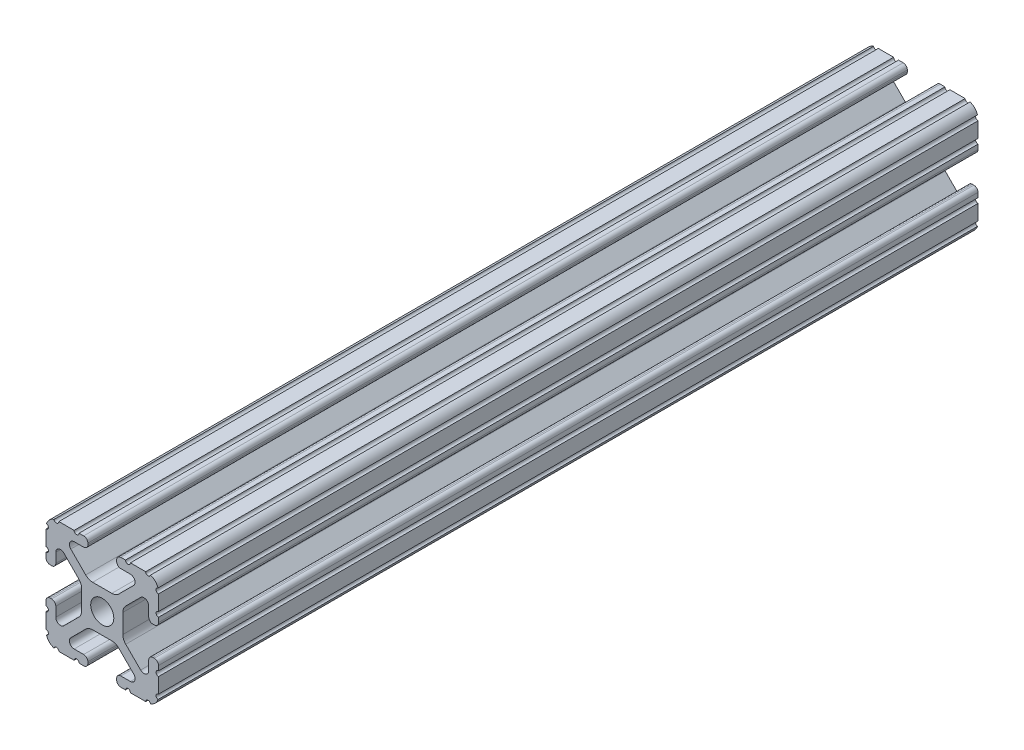
SolidWorks part; units mm, degrees
ref_plane "Front Plane" through (0, 0, 0) normal (0, 0, 1) x (1, 0, 0)
ref_plane "Top Plane" through (0, 0, 0) normal (0, 1, 0) x (1, 0, 0)
ref_plane "Right Plane" through (0, 0, 0) normal (1, 0, 0) x (0, 0, -1)
sketch "Sketch2" plane through (0, 0, 0) normal (0, 0, 1) x (1, 0, 0)
  line L0 (0, 12.7) -> (0, -12.7) construction
  line L1 (-12.7, 0) -> (12.7, 0) construction
  line L2 (3.2512, -12.7) -> (12.7, -12.7)
  line L3 (12.7, -12.7) -> (12.7, -3.2512)
  line L4 (3.2512, -12.7) -> (3.2512, -10.4902)
  line L5 (3.2512, -10.4902) -> (8.9276, -10.4902)
  line L6 (8.9276, -10.4902) -> (3.0856, -4.6482)
  line L7 (0, 0) -> (12.7, -12.7) construction
  line L8 (12.7, -3.2512) -> (10.4902, -3.2512)
  line L9 (10.4902, -3.2512) -> (10.4902, -8.9276)
  line L10 (10.4902, -8.9276) -> (4.6482, -3.0856)
  circle A0 centre (0, 0) radius 2.6035
  arc A1 (6.3485, -10.4902) -> (7.1039, -8.6665) centre (6.3485, -9.4219) ccw construction
  point P8 (0, -4.6482)
  dimension "Center Hole Diameter" = 5.207
  dimension "Rail Height" = 25.4
  dimension "Rail Width" = 25.4
  dimension "T-Slot Width" = 6.5024
  dimension "Slot Inner Width" = 14.8336
  dimension "Thickness" = 2.2098
  dimension "Slot Depth" = 5.842
  dimension "D1" = 2.2098
sketch "Sketch3" plane through (0, 0, 0) normal (1, 0, 0) x (0, 0, -1)
  line L0 (-92.5071, -12.7) -> (92.5071, -12.7) construction
  line L1 (-67.1071, 0) -> (67.1071, 0) construction
  line L2 (92.5071, 0) -> (-92.5071, 0) construction
sketch "Sketch4" plane through (0, 0, 0) normal (0, 0, 1) x (1, 0, 0)
  line L0 (4.1904, -12.7) -> (10.1173, -12.7)
  line L1 (3.2512, -12.7) -> (12.7, -12.7) construction
  line L2 (3.2512, -12.7) -> (3.2512, -10.4902) construction
  line L3 (3.2512, -10.4902) -> (8.9276, -10.4902) construction
  line L4 (3.2512, -11.4294) -> (3.2512, -11.7608)
  line L5 (4.1904, -10.4902) -> (6.3485, -10.4902)
  line L6 (0, -4.6482) -> (2.164, -4.6482)
  line L7 (8.9276, -10.4902) -> (3.0856, -4.6482) construction
  line L8 (3.7373, -5.2999) -> (7.1039, -8.6665)
  line L9 (12.7, -12.7) -> (12.7, -3.2512) construction
  line L10 (10.4902, -8.9276) -> (4.6482, -3.0856) construction
  line L11 (10.4902, -3.2512) -> (10.4902, -8.9276) construction
  line L12 (10.4902, -6.3485) -> (10.4902, -4.1904)
  line L13 (12.7, -3.2512) -> (10.4902, -3.2512) construction
  line L14 (11.4294, -3.2512) -> (11.7608, -3.2512)
  line L15 (12.7, -4.1904) -> (12.7, -10.1173)
  line L16 (8.6665, -7.1039) -> (5.2999, -3.7373)
  line L17 (4.6482, 0) -> (4.6482, -2.164)
  line L18 (-12.7, 0) -> (12.7, 0) construction
  line L19 (0, -4.6482) -> (0, -2.6035)
  line L20 (0, 12.7) -> (0, -12.7) construction
  line L21 (4.6482, 0) -> (2.6035, 0)
  arc A0 (3.2512, -11.7608) -> (4.1904, -12.7) centre (4.1904, -11.7608) ccw
  arc A2 (3.2512, -11.4294) -> (4.1904, -10.4902) centre (4.1904, -11.4294) cw
  arc A3 (6.3485, -10.4902) -> (7.1039, -8.6665) centre (6.3485, -9.4219) ccw
  arc A4 (2.164, -4.6482) -> (3.7373, -5.2999) centre (2.164, -6.8732) cw
  arc A5 (10.1173, -12.7) -> (12.7, -10.1173) centre (10.1173, -10.1173) ccw
  arc A6 (8.6665, -7.1039) -> (10.4902, -6.3485) centre (9.4219, -6.3485) ccw
  arc A7 (10.4902, -4.1904) -> (11.4294, -3.2512) centre (11.4294, -4.1904) cw
  arc A8 (11.7608, -3.2512) -> (12.7, -4.1904) centre (11.7608, -4.1904) cw
  arc A9 (5.2999, -3.7373) -> (4.6482, -2.164) centre (6.8732, -2.164) cw
  circle A10 centre (0, 0) radius 2.6035 construction
  arc A11 (0, -2.6035) -> (2.6035, 0) centre (0, 0) ccw
  dimension "D1" = 2.5827
  dimension "D2" = 2.225
  dimension "D3" = 0.9392
extrude "Boss-Extrude1" add sketch "Sketch4" along normal up to vertex (92.5071 mm away) from vertex at -92.5071 starting at point (0, -12.7, -92.5071)
sketch "Sketch5" plane through (0, 0, 0) normal (0, 0, 1) x (1, 0, 0)
  line L0 (3.2512, -12.7) -> (12.7, -12.7) construction
  line L1 (4.1904, -10.4902) -> (6.3485, -10.4902) construction
  line L3 (0, 0) -> (12.7, -12.7) construction
  line L4 (6.3485, -10.4902) -> (6.3485, -12.7) construction
  line L5 (8.9276, -10.4902) -> (3.0856, -4.6482) construction
  circle A0 centre (10.3562, -12.7) radius 0.5524
  circle A1 centre (5.796, -12.7) radius 0.5524
  circle A2 centre (12.7, -10.3562) radius 0.5524
  circle A3 centre (12.7, -5.796) radius 0.5524
  point P10 (5.2694, -10.4902)
  point P12 (9.4219, -6.3485)
  dimension "D1" = 1.1049
extrude "Cut-Extrude1" cut sketch "Sketch5" against normal through all both and the other way through all
mirror "Mirror1" about plane through (0, 0, 0) normal (1, 0, 0) of bodies 137 134
mirror "Mirror2" about plane through (0, 0, 0) normal (0, 1, 0) of bodies 135
equation "\"D1@Sketch2\"=\"Thickness@Sketch2\""
equation "\"D2@Sketch4\"=\"Slot Inner Width@Sketch2\"*0.15"
equation "\"D1@Sketch4\"=\"D3@Sketch4\"*2.75"
equation "\"D3@Sketch4\"=\"Thickness@Sketch2\"*0.425"
equation "\"D1@Sketch5\"=\"Thickness@Sketch2\"*0.5"
equation "\"D1@Boss-Extrude1\"=\"Length@Sketch3\""
